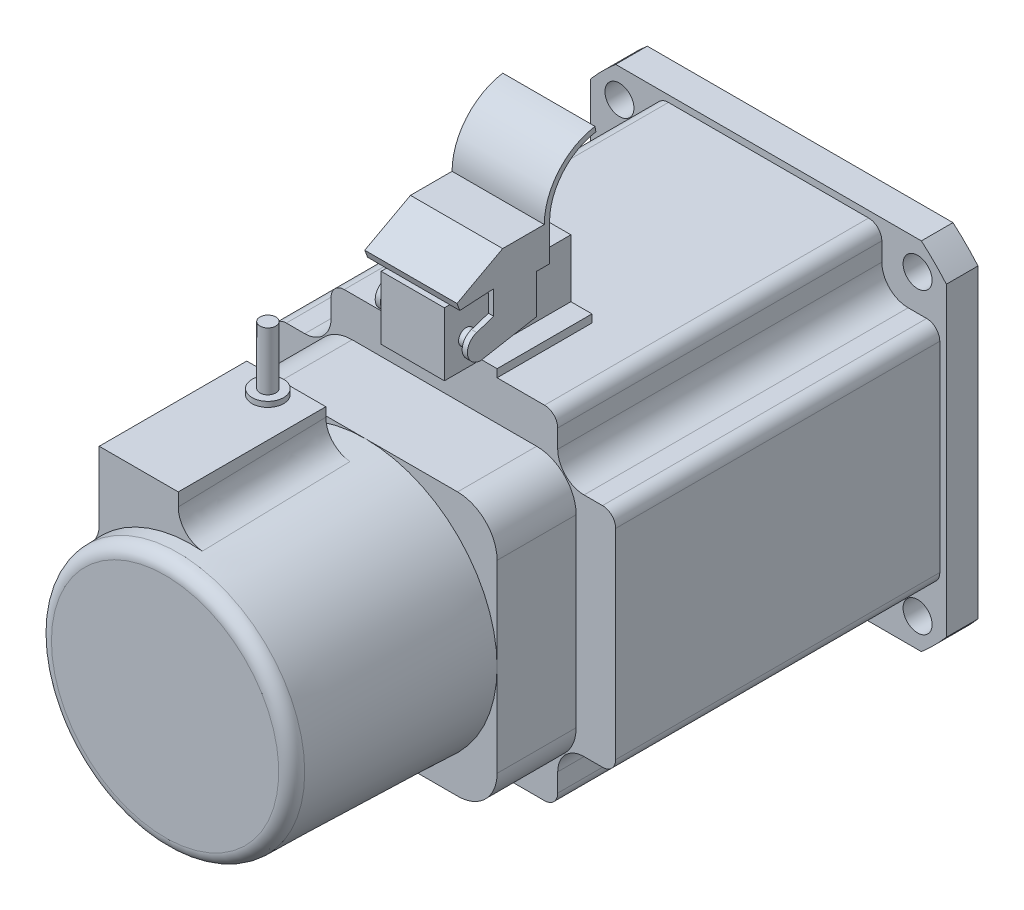
SolidWorks part; units mm, degrees
material "普通碳钢"
ref_plane "前视基准面" through (0, 0, 0) normal (0, 0, 1) x (1, 0, 0)
ref_plane "上视基准面" through (0, 0, 0) normal (0, 1, 0) x (1, 0, 0)
ref_plane "右视基准面" through (0, 0, 0) normal (1, 0, 0) x (0, 0, -1)
sketch "草图1" plane through (0, 0, 0) normal (0, 1, 0) x (1, 0, 0)
  line L0 (0, 0) -> (0, -124.7151) construction
  line L1 (0, 0) -> (0, 55)
  line L2 (0, 55) -> (11, 55)
  line L3 (11, 55) -> (11, 5)
  line L4 (11, 5) -> (14.8, 5)
  line L5 (14.8, 5) -> (14.8, 3)
  line L6 (14.8, 3) -> (57.15, 3)
  line L7 (57.15, 3) -> (57.15, 0)
  line L8 (57.15, 0) -> (0, 0)
  line L9 (0, 0) -> (0.5924, -0.2028)
  dimension "D1" = 22
  dimension "D2" = 29.6
  dimension "D3" = 114.3
  dimension "D4" = 55
  dimension "D5" = 3
  dimension "D6" = 2
revolve "旋转1" add sketch "草图1" angle 360 about L0
sketch "草图2" plane through (0, 0, 0) normal (0, 0, 1) x (1, 0, 0)
  line L1 (-67.5, -67.5) -> (67.5, -67.5)
  line L2 (-67.5, -67.5) -> (-67.5, 67.5)
  line L3 (-67.5, 67.5) -> (67.5, 67.5)
  line L4 (67.5, -67.5) -> (67.5, 67.5)
  line L5 (-67.5, -67.5) -> (67.5, 67.5) construction
  line L6 (-67.5, 67.5) -> (67.5, -67.5) construction
  point P0 (0, 0)
  dimension "D1" = 135
extrude "凸台-拉伸1" add sketch "草图2" along normal blind 12
sketch "草图3" plane through (0, 0, 12) normal (0, 0, 1) x (1, 0, 0)
  line L1 (-65, -65) -> (65, -65)
  line L2 (-65, -65) -> (-65, 65)
  line L3 (-65, 65) -> (65, 65)
  line L4 (65, -65) -> (65, 65)
  line L5 (-65, -65) -> (65, 65) construction
  line L6 (-65, 65) -> (65, -65) construction
  point P0 (0, 0)
  dimension "D1" = 130
extrude "凸台-拉伸2" add sketch "草图3" along normal blind 153
sketch "草图4" plane through (0, 0, 165) normal (0, 0, 1) x (1, 0, 0)
  line L0 (0, 0) -> (0, 89.0371) construction
  line L1 (0, 0) -> (-73.8034, 0) construction
  line L2 (43, 65) -> (43, 43)
  line L3 (-65, 65) -> (-43, 65)
  line L4 (-65, 65) -> (-65, 43)
  line L5 (-65, 43) -> (-43, 43)
  line L6 (-43, 65) -> (-43, 43)
  line L7 (65, 43) -> (43, 43)
  line L8 (65, 65) -> (65, 43)
  line L9 (65, 65) -> (43, 65)
  line L10 (65, -65) -> (43, -65)
  line L11 (65, -65) -> (65, -43)
  line L12 (65, -43) -> (43, -43)
  line L13 (-43, -65) -> (-43, -43)
  line L14 (-65, -43) -> (-43, -43)
  line L15 (-65, -65) -> (-65, -43)
  line L16 (-65, -65) -> (-43, -65)
  line L17 (43, -65) -> (43, -43)
  dimension "D1" = 22
extrude "切除-拉伸1" cut sketch "草图4" against normal blind 153
fillet "圆角1" radius 10 4 edges at (-43, -43, 88.5) (43, -43, 88.5) (43, 43, 88.5) (-43, 43, 88.5)
fillet "圆角2" radius 5 8 edges at (-43, -65, 88.5) (43, -65, 88.5) (65, -43, 88.5) (65, 43, 88.5) (43, 65, 88.5) (-65, -43, 88.5) (-65, 43, 88.5) (-43, 65, 88.5)
ref_plane "基准面1" through (0, 0, 241) normal (0, 0, 1) x (1, 0, 0)
sketch "草图8" plane through (0, 0, 0) normal (0, 1, 0) x (1, 0, 0)
  line L0 (0, 0) -> (0, -266.8555) construction
  line L1 (0, -165) -> (50, -165)
  line L2 (38, -165) -> (-38, -165) construction
  line L3 (50, -165) -> (48, -241)
  line L4 (48, -241) -> (0, -241)
  line L5 (0, -241) -> (0, -165)
  dimension "D1" = 100
  dimension "D2" = 96
  dimension "D3" = 76
revolve "旋转2" add sketch "草图8" angle 360 about L0
ref_plane "基准面2" through (0, 0, 231) normal (0, 0, 1) x (1, 0, 0)
sketch "草图9" plane through (0, 0, 231) normal (0, 0, 1) x (1, 0, 0)
  line L0 (-20, 77.5634) -> (-20, -10.0313) construction
  line L2 (-35, 63) -> (-5, 63)
  line L3 (-35, 63) -> (-35, 25.9039)
  line L4 (-35, 25.9039) -> (-5, 25.9039)
  line L5 (-5, 63) -> (-5, 25.9039)
  dimension "D1" = 20
  dimension "D2" = 63
  dimension "D3" = 30
extrude "凸台-拉伸3" add sketch "草图9" against normal offset from surface (56 mm away) 10 up to face at (0, 0, 165)
fillet "圆角3" radius 10 1 edges
ref_plane "基准面3" through (0, 0, 130) normal (0, 0, 1) x (1, 0, 0)
fillet "圆角4" radius 5 1 edges at (-48, 0, 241)
sketch "草图11" plane through (0, 0, 0) normal (0, 0, -1) x (-1, 0, 0)
  circle A0 centre (0, 0) radius 89
  dimension "D1" = 178
extrude "切除-拉伸2" cut sketch "草图11" against normal blind 48 flip side to cut
sketch "草图12" plane through (0, 0, 0) normal (0, 0, -1) x (-1, 0, 0)
  line L0 (0, 0) -> (-56.5685, 56.5685) construction
  line L2 (0, 0) -> (-52.6592, 0) construction
  circle A0 centre (-56.5685, 56.5685) radius 5.5
  circle A1 centre (0, 0) radius 80 construction
  dimension "D1" = 160
  dimension "D2" = 11
  dimension "D3" = 45
extrude "切除-拉伸3" cut sketch "草图12" against normal blind 48
pattern_circular "阵列(圆周)1" count 4 over 360 about axis through (0, 0, 0) along (0, 0, 1) of "切除-拉伸3"
chamfer "倒角2" distance 1 angle 45 1 edges at (-11, 0, -55)
sketch "草图14" plane through (0, 0, 0) normal (0, 1, 0) x (1, 0, 0)
  line L0 (0, 49) -> (0, 13) construction
  line L1 (3, 49) -> (3, 13)
  line L2 (-3, 49) -> (-3, 13)
  line L5 (10, 55) -> (-10, 55) construction
  arc A0 (3, 49) -> (-3, 49) centre (0, 49) ccw
  arc A1 (-3, 13) -> (3, 13) centre (0, 13) ccw
  point P3 (0, 31)
  dimension "D2" = 3
  dimension "D3" = 42
  dimension "D1" = 6
extrude "切除-拉伸4" cut sketch "草图14" against normal up to next from offset 8.5 offset against normal yes
sketch "草图15" plane through (0, 0, 0) normal (0, 1, 0) x (1, 0, 0)
  line L0 (0, 49) -> (0, 13) construction
  line L1 (3, 49) -> (3, 13)
  line L2 (-3, 49) -> (-3, 13)
  line L3 (10, 55) -> (-10, 55) construction
  arc A0 (3, 49) -> (-3, 49) centre (0, 49) ccw
  arc A1 (-3, 13) -> (3, 13) centre (0, 13) ccw
  point P3 (0, 31)
  dimension "D1" = 3
  dimension "D2" = 42
  dimension "D3" = 6
extrude "凸台-拉伸5" add sketch "草图15" along normal blind 13.5
fillet "圆角5" radius 2.5 1 edges at (-11, 0, -5)
sketch "草图17" plane through (0, 0, 165) normal (0, 0, 1) x (1, 0, 0)
  line L1 (-35, -50) -> (35, -50)
  line L2 (-50, -35) -> (-50, 35)
  line L3 (-35, 50) -> (35, 50)
  line L4 (50, -35) -> (50, 35)
  line L5 (-50, -50) -> (50, 50) construction
  line L6 (-50, 50) -> (50, -50) construction
  arc A0 (-50, -35) -> (-35, -50) centre (-35, -35) ccw
  arc A1 (35, -50) -> (50, -35) centre (35, -35) ccw
  arc A2 (50, 35) -> (35, 50) centre (35, 35) ccw
  arc A3 (-35, 50) -> (-50, 35) centre (-35, 35) ccw
  point P0 (0, 0)
  dimension "D2" = 15
  dimension "D1" = 100
extrude "切除-拉伸5" cut sketch "草图17" against normal blind 30 flip side to cut
fillet "圆角6" radius 10 1 edges
sketch "草图19" plane through (0, 0, 0) normal (1, 0, 0) x (0, 0, -1)
  line L0 (0, 58.0065) -> (0, 67.5) construction
  line L1 (-147, 90) -> (-99, 90)
  line L2 (-147, 90) -> (-147, 66)
  line L3 (-147, 66) -> (-99, 66)
  line L4 (-99, 90) -> (-99, 66)
  line L6 (-135, 65) -> (-12, 65) construction
  dimension "D1" = 99
  dimension "D2" = 48
  dimension "D3" = 24
  dimension "D4" = 1
extrude "凸台-拉伸6" add sketch "草图19" along normal mid plane 24
sketch "草图20" plane through (0, 0, 135) normal (0, 0, 1) x (1, 0, 0)
  line L0 (0, 0) -> (0, 115.2988) construction
  line L1 (38, 65) -> (-38, 65) construction
  line L2 (-20, 65) -> (20, 65)
  line L3 (-20, 65) -> (-20, 68)
  line L4 (-20, 68) -> (20, 68)
  line L5 (20, 65) -> (20, 68)
  dimension "D1" = 3
  dimension "D2" = 40
extrude "凸台-拉伸7" add sketch "草图20" against normal up to surface (36 mm away) up to face at (0, 78, 99)
sketch "草图21" plane through (0, 0, 0) normal (1, 0, 0) x (0, 0, -1)
  line L0 (-99, 90) -> (-147, 90) construction
  line L11 (-133.792, 83.3561) -> (-140.2438, 81.244)
  line L12 (-133.792, 92.4297) -> (-133.792, 83.3561)
  line L13 (-146.6497, 91.688) -> (-133.792, 92.4297)
  line L14 (-147.7178, 94.5363) -> (-146.6497, 91.688)
  line L15 (-130.3904, 103.9121) -> (-147.7178, 94.5363)
  line L16 (-112.5882, 103.9121) -> (-130.3904, 103.9121)
  line L17 (-112.5882, 90) -> (-112.5882, 103.9121)
  line L18 (-117.4541, 90) -> (-112.5882, 90)
  line L19 (-117.4541, 75.11) -> (-117.4541, 90)
  line L20 (-138.6536, 71.2748) -> (-117.4541, 75.11)
  arc A1 (-138.6536, 71.2748) -> (-140.2438, 81.244) centre (-138.6537, 76.3863) cw
extrude "凸台-拉伸8" add sketch "草图21" along normal mid plane 35
sketch "草图22" plane through (0, 0, 0) normal (1, 0, 0) x (0, 0, -1)
  line L1 (-112.5882, 90) -> (-112.5882, 103.9121) construction
  arc A0 (-112.5882, 103.9121) -> (-95.0242, 124.5843) centre (-91.641, 103.9121) cw
extrude "拉伸-薄壁1" add sketch "草图22" along normal mid plane 35 thin thin type one direction reverse wall 2
sketch "草图23" plane through (0, 63, 0) normal (0, 1, 0) x (1, 0, 0)
  line L0 (12, -147) -> (-12, -147) construction
  circle A0 centre (-20, -182) radius 6
  dimension "D1" = 35
  dimension "D2" = 12
  dimension "D3" = 20
extrude "凸台-拉伸9" add sketch "草图23" along normal blind 2
sketch "草图24" plane through (0, 65, 0) normal (0, 1, 0) x (1, 0, 0)
  circle A0 centre (-20, -182) radius 3
  dimension "D1" = 6
extrude "凸台-拉伸10" add sketch "草图24" along normal blind 22
sketch "草图25" plane through (0, 0, 147) normal (0, 0, 1) x (1, 0, 0)
  line L0 (0, 0) -> (0, 126.4467) construction
  line L1 (-12, 71.2748) -> (-15.5, 71.2748)
  line L2 (-12, 71.2748) -> (-12, 89.9335)
  line L3 (-12, 89.9335) -> (-15.5, 89.9335)
  line L4 (-15.5, 71.2748) -> (-15.5, 89.9335)
  line L5 (15.5, 71.2748) -> (15.5, 89.9335)
  line L6 (12, 89.9335) -> (15.5, 89.9335)
  line L7 (12, 71.2748) -> (12, 89.9335)
  line L8 (12, 71.2748) -> (15.5, 71.2748)
  line L10 (-12, 71.2748) -> (-17.5, 71.2748) construction
  line L11 (-12, 90) -> (-12, 66) construction
extrude "切除-拉伸6" cut sketch "草图25" against normal through all
sketch "草图27" plane through (-17.5, 0, 0) normal (-1, 0, 0) x (0, 0, 1)
  circle A0 centre (138.6537, 76.3863) radius 2.9861
extrude "凸台-拉伸11" add sketch "草图27" against normal up to surface (35 mm away)
chamfer "倒角3" distance 0.5 angle 45 1 edges at (-57.15, 0, -3)
hole_wizard "M6 螺纹孔1" positions "草图29" profile "草图28" tap size "M6" standard "GB"
sketch "草图29" plane through (0, 0, -55) normal (0, 0, -1) x (-1, 0, 0)
  point P0 (0, 0)
cosmetic thread "孔螺蚊线1" parameters "D1"=6, "D2"=6
sketch "草图28" plane through (0, 0, -55) normal (1, 0, 0) x (0, 1, 0)
  line L0 (0, 0) -> (0, 12.5022)
  line L1 (0, 12.5022) -> (2.5, 11)
  line L2 (2.5, 11) -> (2.5, 0)
  line L5 (2.5, 0) -> (0, 0)
  line L10 (0, 12.5022) -> (-2.5, 11) construction
  line L11 (0, -6.35) -> (0, 107.95) construction
  dimension "螺纹孔钻头直径" = 5
  dimension "螺纹孔钻头深度" = 11
  dimension "导头角度" = 118
